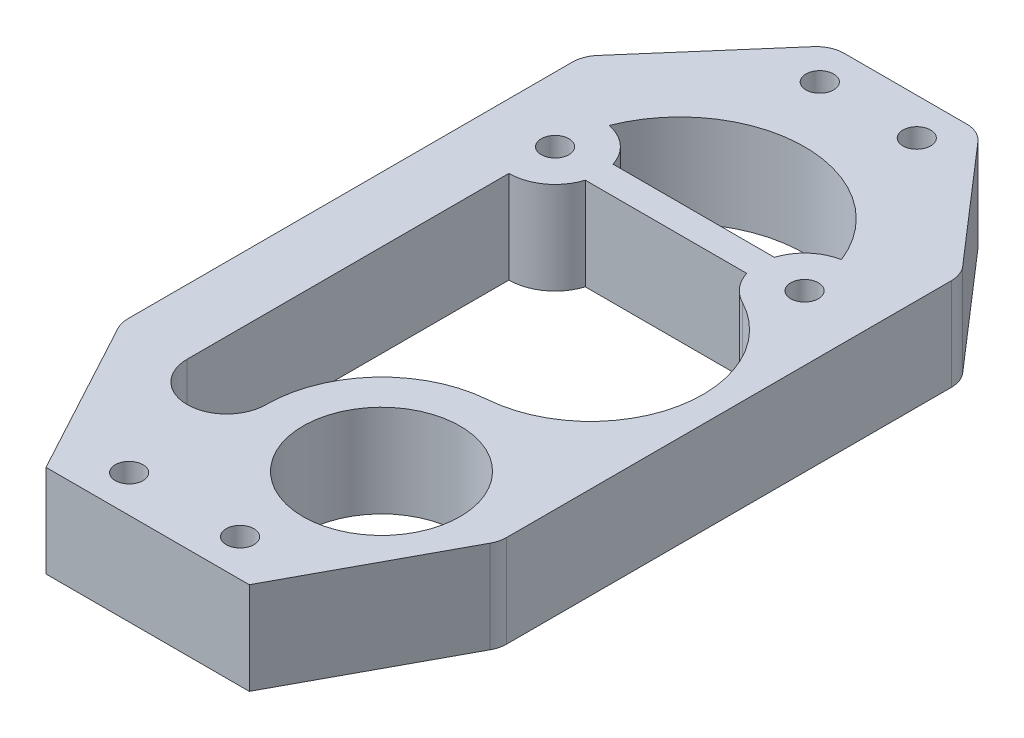
SolidWorks part; units mm, degrees
ref_plane "Front" through (0, 0, 0) normal (0, 0, 1) x (1, 0, 0)
ref_plane "Top" through (0, 0, 0) normal (0, 1, 0) x (1, 0, 0)
ref_plane "Right" through (0, 0, 0) normal (1, 0, 0) x (0, 0, -1)
sketch "Sketch1" plane through (0, 0, 0) normal (0, 1, 0) x (1, 0, 0)
  line L0 (0, 24.4003) -> (0, 0) construction
  line L1 (0, 0) -> (-13.5, 0) construction
  line L2 (8, 24.4003) -> (-8, 24.4003)
  line L3 (-8, 24.4003) -> (-20.5, 10)
  line L4 (-20.5, 10) -> (-20.5, -40)
  line L5 (-20.5, -40) -> (-11, -57.5997)
  line L6 (-11, -57.5997) -> (11, -57.5997)
  line L7 (20.5, -40) -> (11, -57.5997)
  line L8 (20.5, 10) -> (20.5, -40)
  line L9 (8, 24.4003) -> (20.5, 10)
  line L11 (7.5302, -39.8174) -> (17.65, -45.2799) construction
  line L12 (-13.5, -5) -> (-13.5, -39.8174)
  line L13 (8.7303, -1.5) -> (-8.7303, -1.5)
  line L15 (8.7303, 1.5) -> (-8.7303, 1.5)
  line L17 (8.7303, -1.5) -> (-8.7303, 1.5) construction
  line L18 (8.7303, 1.5) -> (-8.7303, -1.5) construction
  arc A0 (12.5741, 4.9135) -> (-12.5741, 4.9135) centre (0, 0) ccw
  circle A1 centre (-5.25, 20.3945) radius 1.5
  circle A2 centre (-6, -53.5997) radius 1.5
  circle A3 centre (6, -53.5997) radius 1.5
  circle A4 centre (5.25, 20.3945) radius 1.5
  arc A5 (-13.5, -5) -> (-8.7303, -1.5) centre (-13.5, 0) ccw
  arc A6 (8.7303, -1.5) -> (11.188, -4.4333) centre (13.5, 0) ccw
  circle A7 centre (-13.5, 0) radius 1.5
  circle A8 centre (13.5, 0) radius 1.5
  arc A9 (-13.5, -39.8174) -> (-4.9698, -39.8174) centre (-9.2349, -39.8174) ccw
  arc A10 (-4.9698, -39.8174) -> (6.5319, -27.3573) centre (7.5302, -39.8174) cw
  arc A11 (6.5319, -27.3573) -> (11.188, -4.4333) centre (5.56, -15.2251) ccw
  circle A12 centre (7.5302, -39.8174) radius 8.5
  arc A13 (-8.7303, 1.5) -> (-12.5741, 4.9135) centre (-13.5, 0) ccw
  arc A14 (12.5741, 4.9135) -> (8.7303, 1.5) centre (13.5, 0) ccw
  point P15 (0, -57.5997)
  dimension "D5" = 3
  dimension "D6" = 4
  dimension "D7" = 10.5
  dimension "D8" = 3
  dimension "D10" = 17
  dimension "D15" = 4
  dimension "D16" = 10
  dimension "D17" = 13.5
  dimension "D18" = 3
  dimension "D19" = 3
  dimension "D23" = 12
  dimension "D24" = 22
  dimension "D2" = 41
  dimension "D3" = 16
  dimension "D4" = 22
  dimension "D9" = 11.5
  dimension "D11" = 6
  dimension "D12" = 20
  dimension "D13" = 50
  dimension "D14" = 10
  dimension "D20" = 3
  dimension "D21" = 45
  dimension "D22" = 13.5
extrude "Boss-Extrude1" add sketch "Sketch1" along normal mid plane 10
fillet "Fillet1" radius 3 6 edges at (-20.5, 0, 40) (-20.5, 0, -10) (-8, 0, -24.4003) (8, 0, -24.4003) (20.5, 0, -10) (20.5, 0, 40)
